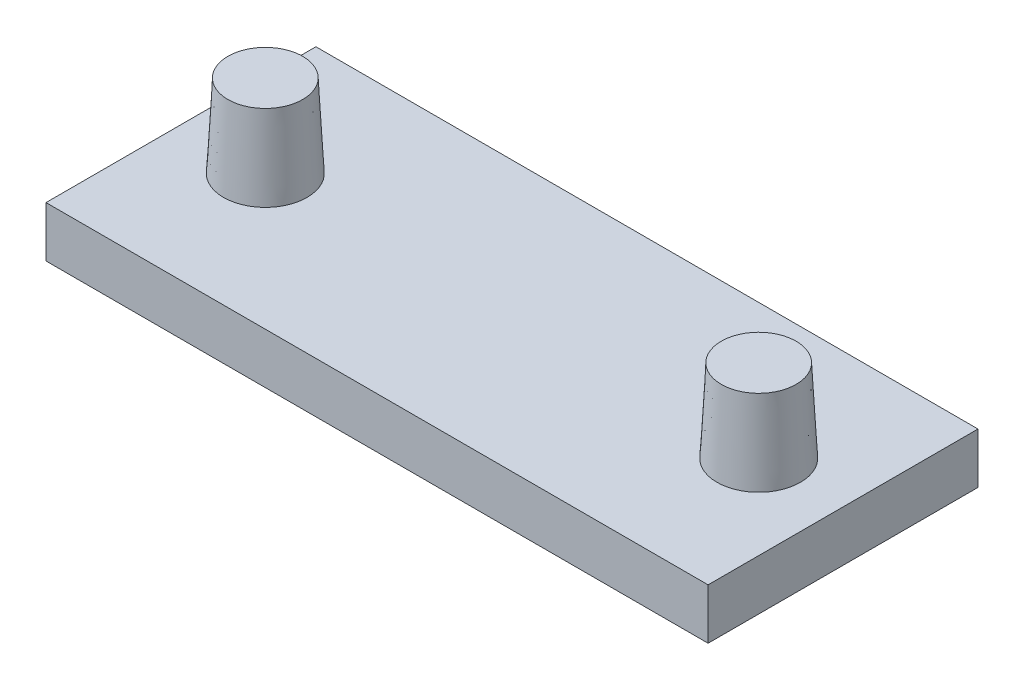
SolidWorks part; units mm, degrees
ref_plane "Front Plane" through (0, 0, 0) normal (0, 0, 1) x (1, 0, 0)
ref_plane "Top Plane" through (0, 0, 0) normal (0, 1, 0) x (1, 0, 0)
ref_plane "Right Plane" through (0, 0, 0) normal (1, 0, 0) x (0, 0, -1)
sketch "Sketch1" plane through (0, 0, 0) normal (0, 1, 0) x (1, 0, 0)
  line L0 (0.8266, 5.1023) -> (30.0766, 5.1023) construction
  line L2 (-4.1734, -2.8977) -> (35.0766, -2.8977)
  line L3 (-4.1734, -2.8977) -> (-4.1734, 13.1023)
  line L4 (-4.1734, 13.1023) -> (35.0766, 13.1023)
  line L5 (35.0766, -2.8977) -> (35.0766, 13.1023)
  dimension "D2" = 5
  dimension "D1" = 29.25
  dimension "D3" = 5
  dimension "D4" = 8
  dimension "D5" = 8
extrude "Boss-Extrude1" add sketch "Sketch1" along normal blind 3
sketch "Sketch2" plane through (0, 3, 0) normal (0, 1, 0) x (1, 0, 0)
  circle A0 centre (0.8266, 5.1023) radius 2.475
  circle A1 centre (30.0766, 5.1023) radius 2.475
  dimension "D1" = 4.95
  dimension "D2" = 4.95
extrude "Boss-Extrude2" add sketch "Sketch2" along normal blind 4.9 draft 3
